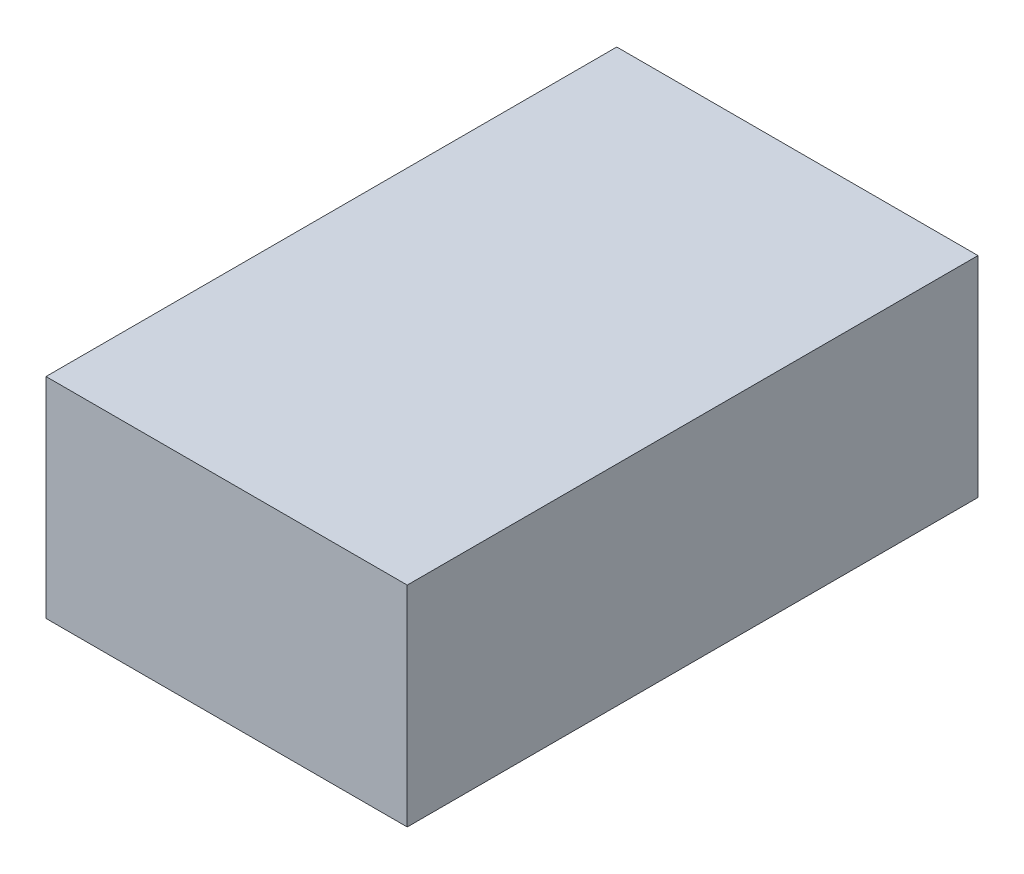
SolidWorks part; units mm, degrees
ref_plane "Front Plane" through (0, 0, 0) normal (0, 0, 1) x (1, 0, 0)
ref_plane "Top Plane" through (0, 0, 0) normal (0, 1, 0) x (1, 0, 0)
ref_plane "Right Plane" through (0, 0, 0) normal (1, 0, 0) x (0, 0, -1)
sketch "Sketch4" plane through (0, 0, 0) normal (0, 1, 0) x (1, 0, 0)
  line L0 (-80.5364, 173.4511) -> (-80.5364, -131.5489)
  line L1 (79.4636, -131.5489) -> (-80.5364, -131.5489)
  line L2 (79.4636, 173.4511) -> (79.4636, -131.5489)
  line L3 (-125.5364, 218.171) -> (-125.5364, -176.829)
  line L4 (124.4636, -176.829) -> (-125.5364, -176.829)
  line L5 (124.4636, 218.171) -> (124.4636, -176.829)
  line L6 (-125.5364, 218.171) -> (124.4636, 218.171)
  line L7 (-80.5364, 173.4511) -> (79.4636, 173.4511)
  point P0 (-43.0364, -31.5994)
  point P13 (0, 0)
extrude "Boss-Extrude4" add sketch "Sketch4" along normal blind 145 contours L5 L4 L3 L6
